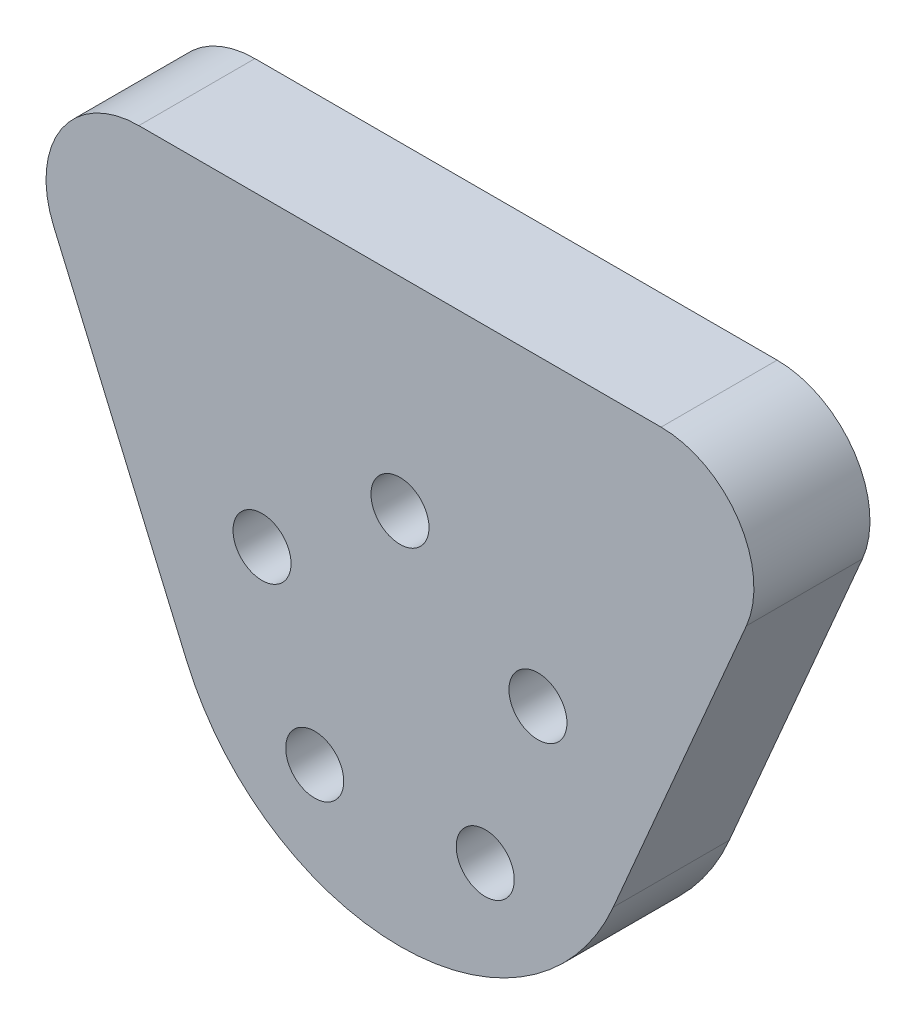
SolidWorks part; units mm, degrees
ref_plane "Alzado" through (0, 0, 0) normal (0, 0, 1) x (1, 0, 0)
ref_plane "Planta" through (0, 0, 0) normal (0, 1, 0) x (1, 0, 0)
ref_plane "Vista lateral" through (0, 0, 0) normal (1, 0, 0) x (0, 0, -1)
sketch "Croquis1" plane through (0, 0, 0) normal (0, 0, 1) x (1, 0, 0)
  line L0 (-45, 8) -> (0, 8)
  line L1 (-52.3516, -3.155) -> (-40.879, -29.8876)
  line L2 (7.3516, -3.155) -> (-4.121, -29.8876)
  line L3 (-22.5, 8) -> (-22.5, -22) construction
  arc A0 (7.3516, -3.155) -> (0, 8) centre (0, 0) ccw
  arc A1 (-45, 8) -> (-52.3516, -3.155) centre (-45, 0) ccw
  arc A2 (-40.879, -29.8876) -> (-4.121, -29.8876) centre (-22.5, -22) ccw
  circle A3 centre (-22.5, -22) radius 12.5 construction
  circle A4 centre (-22.5, -9.5) radius 2.5
  circle A5 centre (-10.6118, -18.1373) radius 2.5
  circle A6 centre (-15.1527, -32.1127) radius 2.5
  circle A7 centre (-29.8473, -32.1127) radius 2.5
  circle A8 centre (-34.3882, -18.1373) radius 2.5
  point P25 (-22.5, -22)
  dimension "D1" = 20
  dimension "D2" = 8
  dimension "D5" = 25
  dimension "D6" = 5
  dimension "D3" = 45
  dimension "D4" = 30
  dimension "D7" = 5
extrude "Saliente-Extruir1" add sketch "Croquis1" along normal blind 10
